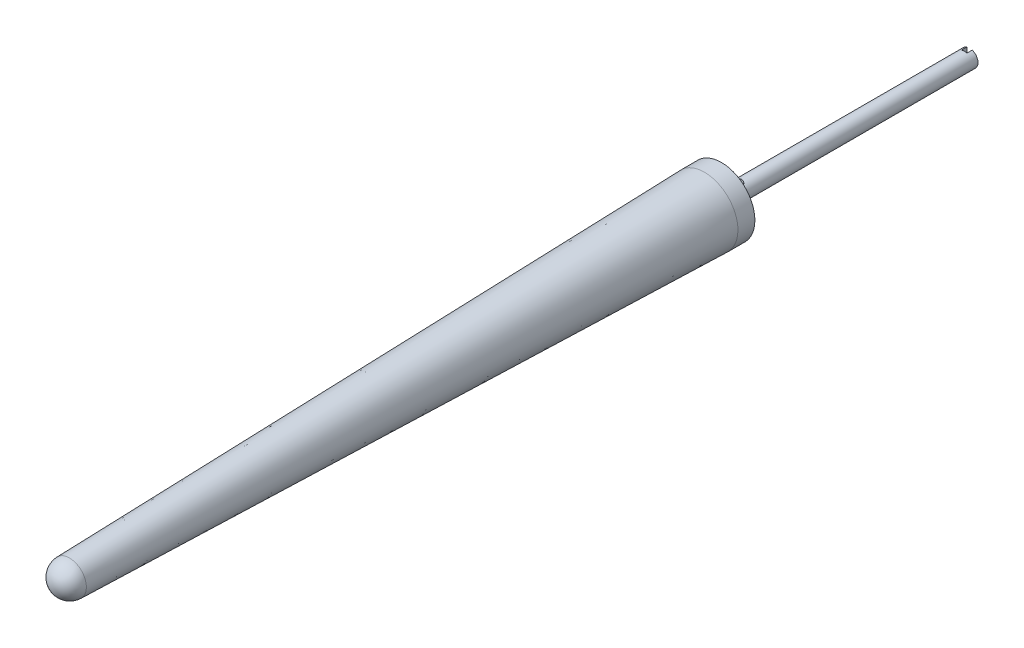
SolidWorks part; units mm, degrees
ref_plane "Front Plane" through (0, 0, 0) normal (0, 0, 1) x (1, 0, 0)
ref_plane "Top Plane" through (0, 0, 0) normal (0, 1, 0) x (1, 0, 0)
ref_plane "Right Plane" through (0, 0, 0) normal (1, 0, 0) x (0, 0, -1)
sketch "Sketch1" plane through (0, 0, 0) normal (1, 0, 0) x (0, 0, -1)
  line L0 (0, 0) -> (-276.4, 0) construction
  line L1 (0, 0) -> (0, 2.555)
  line L2 (0, 2.555) -> (-74.8, 2.555)
  line L3 (-74.8, 2.555) -> (-74.8, 10.07)
  line L4 (-79.91, 10.07) -> (-271.4223, 5.1083)
  line L5 (0, 0) -> (-276.4, 0)
  line L6 (-74.8, 10.07) -> (-79.91, 10.07)
  line L7 (-271.4223, 5.1083) -> (-271.29, 0) construction
  arc A1 (-271.4223, 5.1083) -> (-276.4, 0) centre (-271.29, 0) ccw
  dimension "D3" = 5.11
  dimension "D1" = 5.11
  dimension "D2" = 74.8
  dimension "D4" = 201.6
  dimension "D5" = 20.14
  dimension "D6" = 5.11
revolve "Revolve2" add sketch "Sketch1" angle 360 about L0
sketch "Sketch2" plane through (0, 0, 0) normal (0, 0, -1) x (-1, 0, 0)
  line L0 (0.81, 2.4232) -> (0.81, -2.4232)
  line L1 (-0.81, -2.4232) -> (-0.81, 2.4232)
  circle A0 centre (0, 0) radius 2.555 construction
  circle A1 centre (0, 0) radius 2.555 construction
  circle A2 centre (0, 0) radius 2.555
  circle M4 centre (0, 0) radius 2.555
  dimension "D1" = 1.62
  dimension "D2" = 0.81
extrude "Cut-Extrude1" cut sketch "Sketch2" against normal blind 1.62 contours L1 L0 M4
ref_plane "Plane1" through (0, 2.555, 0) normal (0, 1, 0) x (1, 0, 0)
sketch "Sketch3" plane through (0, 2.555, 0) normal (0, 1, 0) x (1, 0, 0)
  line L0 (-2.555, -74.8) -> (2.555, -74.8)
  line L1 (10.07, -74.8) -> (-10.07, -74.8) construction
  line L2 (2.555, -74.8) -> (2.555, 0) construction
  line L3 (-2.555, 0) -> (-2.555, -74.8) construction
  circle A0 centre (0, -70.175) radius 1.5
  dimension "D1" = 3
  dimension "D2" = 4.625
extrude "Cut-Extrude2" cut sketch "Sketch3" against normal blind 2 contours A0
